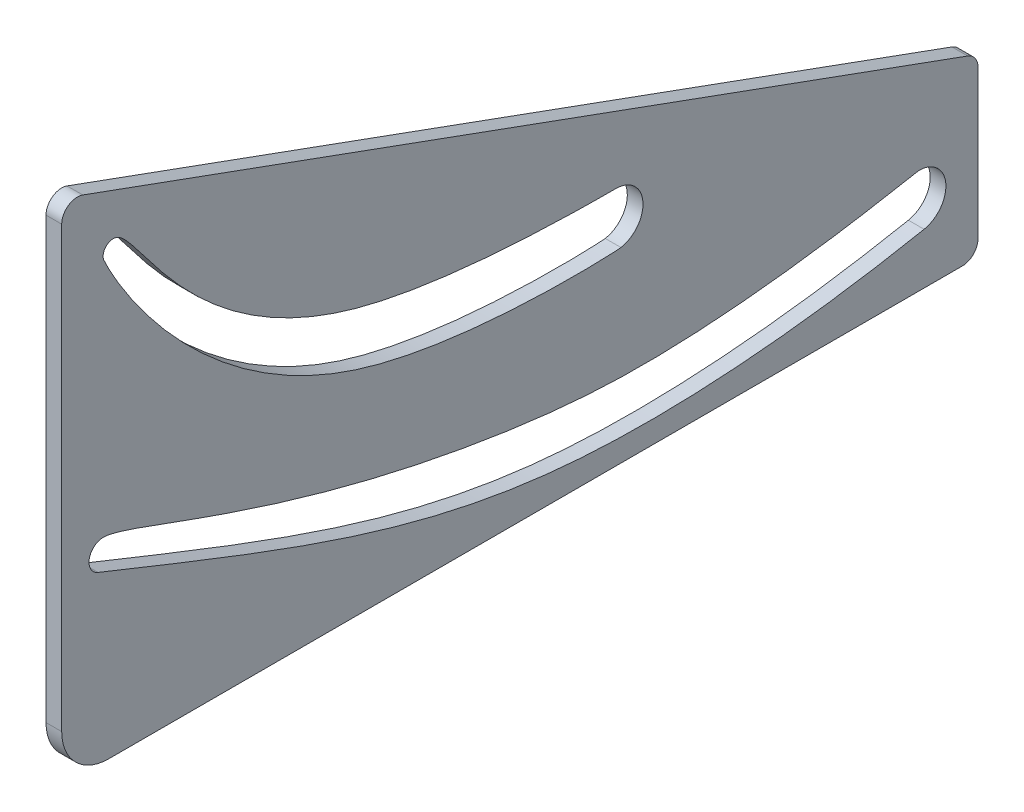
SolidWorks part; units mm, degrees
material "Hexcel AS4C (3000 Filaments)"
ref_plane "Front Plane" through (0, 0, 0) normal (0, 0, 1) x (1, 0, 0)
ref_plane "Top Plane" through (0, 0, 0) normal (0, 1, 0) x (1, 0, 0)
ref_plane "Right Plane" through (0, 0, 0) normal (1, 0, 0) x (0, 0, -1)
sketch "Sketch1" plane through (0, 0, 0) normal (1, 0, 0) x (0, 0, -1)
  line L0 (0, -14.2815) -> (0, -294.2815)
  line L1 (0, 29.2892) -> (0, -29.2892) construction
  line L2 (30, -324.2815) -> (573.8156, -324.2815)
  line L3 (583.8156, -314.2815) -> (583.8156, -219.4936)
  line L4 (577.2358, -210.0966) -> (13.4202, -4.8846)
  arc A0 (30, -324.2815) -> (0, -294.2815) centre (30, -294.2815) cw
  arc A1 (573.8156, -324.2815) -> (583.8156, -314.2815) centre (573.8156, -314.2815) ccw
  arc A2 (583.8156, -219.4936) -> (577.2358, -210.0966) centre (573.8156, -219.4936) ccw
  arc A3 (13.4202, -4.8846) -> (0, -14.2815) centre (10, -14.2815) ccw
  point P9 (0, -324.2815)
  point P16 (0, 0)
  dimension "D2" = 30
  dimension "D3" = 10
  dimension "D1" = 70
  dimension "D4" = 280
  dimension "D5" = 600
extrude "Boss-Extrude1" add sketch "Sketch1" along normal blind 10
sketch "Sketch2" plane through (10, 0, 0) normal (1, 0, 0) x (0, 0, -1)
  arc A0 (23.1622, -218.0173) -> (26.7381, -200.3183) centre (26.5742, -209.4959) cw
  arc A1 (549.474, -291.831) -> (546.1549, -257.731) centre (546.1581, -274.9423) ccw
  arc A2 (26.9502, -47.7372) -> (35.1249, -39.1544) centre (32.8168, -45.1404) cw
  arc A3 (356.3201, -205.3163) -> (353.1695, -171.1817) centre (353.1695, -188.3944) ccw
  spline S0 degree 3 poles (23.1622, -218.0173) (143.0808, -266.0342) (284.6699, -324.5722) (474.7501, -306.5023) (549.474, -291.831) knots 0 0 0 0 0.576112 1 1 1 1
  spline S1 degree 3 poles (26.7381, -200.3183) (45.9144, -200.6608) (151.3211, -255.5104) (414.8803, -286.3851) (542.4311, -257.7317) (546.1549, -257.731) knots 0 0 0 0 0.560935 0.660935 1 1 1 1
  spline S2 degree 3 poles (26.9502, -47.7372) (35.3127, -66.6296) (121.3965, -217.9891) (352.8389, -205.9644) (356.3201, -205.3163) knots 0 0 0 0 0.590315 1 1 1 1
  spline S3 degree 3 poles (35.1249, -39.1544) (50.603, -45.1224) (99.0425, -170.6619) (331.224, -171.1817) (353.1695, -171.1817) knots 0 0 0 0 0.639196 1 1 1 1
sketch "Sketch3" plane through (0, 0, 0) normal (-1, 0, 0) x (0, 0, 1)
  arc A2 (-23.1622, -218.0173) -> (-26.7381, -200.3183) centre (-26.5742, -209.4959) ccw
  arc A3 (-546.1549, -257.731) -> (-549.474, -291.831) centre (-546.1581, -274.9423) ccw
  arc A4 (-23.1622, -218.0173) -> (-26.7381, -200.3183) centre (-26.5742, -209.4959) ccw
  arc A5 (-546.1549, -257.731) -> (-549.474, -291.831) centre (-546.1581, -274.9423) ccw
  arc A6 (-26.9502, -47.7372) -> (-35.1249, -39.1544) centre (-32.8168, -45.1404) ccw
  arc A7 (-353.1695, -171.1817) -> (-356.3201, -205.3163) centre (-353.1695, -188.3944) ccw
  arc A8 (-26.9502, -47.7372) -> (-35.1249, -39.1544) centre (-32.8168, -45.1404) ccw
  arc A9 (-353.1695, -171.1817) -> (-356.3201, -205.3163) centre (-353.1695, -188.3944) ccw
  spline S2 degree 3 poles (-3419.3565, -5140.7703) (-36.1209, 443.9633) (374.3076, -193.9356) (-690.3402, -318.6538) (-1216.7166, 117.8541) (5103.4549, -2273.726) knots -1.994347 -1.994347 -1.994347 -1.994347 0.560935 0.660935 2.045153 2.045153 2.045153 2.045153 only from (-26.7381, -200.3183) to (-546.1549, -257.731)
  spline S3 degree 3 poles (5252.2854, -1738.3158) (-2214.0806, 613.6942) (12.9779, -1093.8356) (243.6841, 352.543) (5925.2449, 337.7798) knots -3.237942 -3.237942 -3.237942 -3.237942 0.423888 3.178404 3.178404 3.178404 3.178404 only from (-549.474, -291.831) to (-23.1622, -218.0173)
  spline S4 degree 3 poles (-26.7381, -200.3183) (-45.9144, -200.6608) (-151.3211, -255.5104) (-414.8803, -286.3851) (-542.4311, -257.7317) (-546.1549, -257.731) knots 0 0 0 0 0.560935 0.660935 1 1 1 1
  spline S5 degree 3 poles (-549.474, -291.831) (-474.7501, -306.5023) (-284.6699, -324.5722) (-143.0808, -266.0342) (-23.1622, -218.0173) knots 0 0 0 0 0.423888 1 1 1 1
  spline S6 degree 3 poles (1435.3971, -5852.166) (-579.4798, 942.5614) (765.2957, -648.0698) (-1228.6743, 33.0101) (5603.0999, -886.0157) knots -1.980564 -1.980564 -1.980564 -1.980564 0.639196 2.282163 2.282163 2.282163 2.282163 only from (-35.1249, -39.1544) to (-353.1695, -171.1817)
  spline S7 degree 3 poles (5552.2297, -1239.4002) (-1165.6083, 83.0763) (541.7196, -813.669) (-218.5971, 1063.2342) (-957.3998, -5967.4028) knots -1.258507 -1.258507 -1.258507 -1.258507 0.409685 2.861715 2.861715 2.861715 2.861715 only from (-356.3201, -205.3163) to (-26.9502, -47.7372)
  spline S8 degree 3 poles (-35.1249, -39.1544) (-50.603, -45.1224) (-99.0425, -170.6619) (-331.224, -171.1817) (-353.1695, -171.1817) knots 0 0 0 0 0.639196 1 1 1 1
  spline S9 degree 3 poles (-356.3201, -205.3163) (-352.8389, -205.9644) (-121.3965, -217.9891) (-35.3127, -66.6296) (-26.9502, -47.7372) knots 0 0 0 0 0.409685 1 1 1 1
  dimension "D1" = 0
  dimension "D2" = 0
extrude "Cut-Extrude3" cut sketch "Sketch3" against normal blind 33
